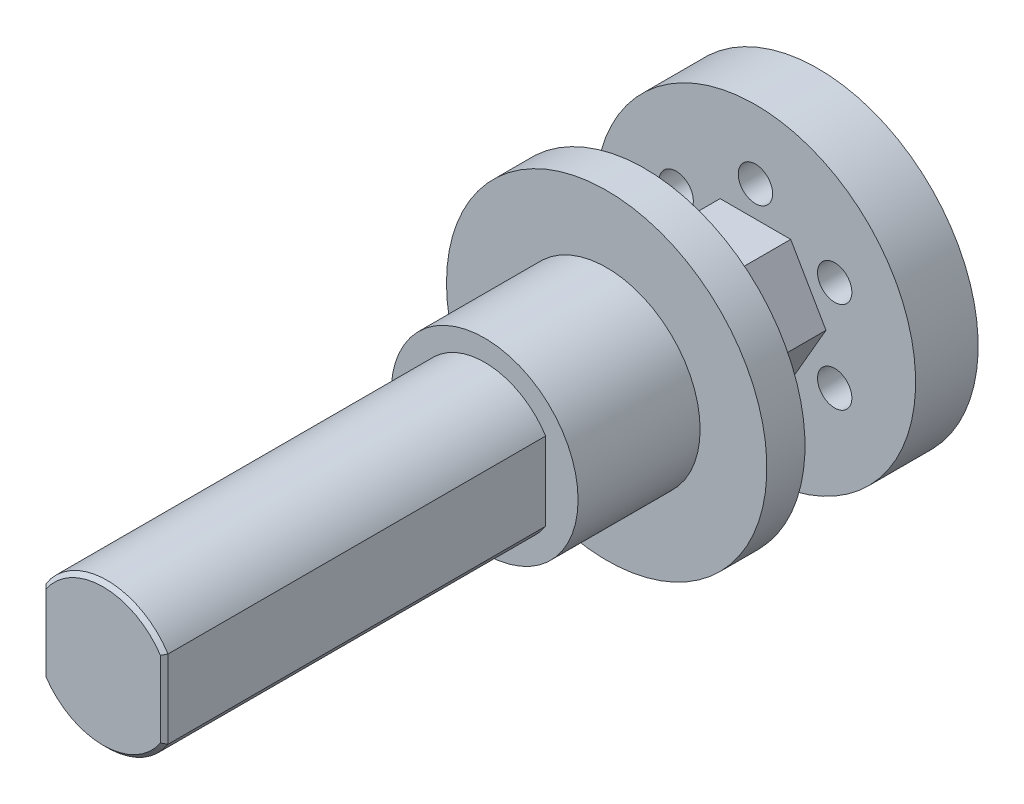
SolidWorks part; units mm, degrees
ref_plane "前视基准面" through (0, 0, 0) normal (0, 0, 1) x (1, 0, 0)
ref_plane "上视基准面" through (0, 0, 0) normal (0, 1, 0) x (1, 0, 0)
ref_plane "右视基准面" through (0, 0, 0) normal (1, 0, 0) x (0, 0, -1)
other "Configuration Table"
sketch "草图1" plane through (0, 0, 0) normal (0, 0, 1) x (1, 0, 0)
  circle A0 centre (0, 0) radius 9.25
  dimension "D1" = 18.5
extrude "凸台-拉伸1" add sketch "草图1" along normal blind 89.5 contours A0
ref_plane "基准面1" through (11.75, 0, 0) normal (-1, 0, 0) x (0, 0, 1)
ref_plane "基准面2" through (0, 0, 39.5) normal (0, 0, 1) x (1, 0, 0)
sketch "草图4" plane through (0, 0, 39.5) normal (0, 0, 1) x (1, 0, 0)
  circle A0 centre (0, 0) radius 12.25
  dimension "D1" = 24.5
extrude "凸台-拉伸2" add sketch "草图4" against normal blind 16
sketch "草图5" plane through (0, 0, 23.5) normal (0, 0, -1) x (-1, 0, 0)
  circle A0 centre (0, 0) radius 21
  dimension "D1" = 42
extrude "凸台-拉伸3" add sketch "草图5" along normal blind 5
sketch "草图6" plane through (0, 0, 0) normal (0, 0, -1) x (-1, 0, 0)
  circle A0 centre (0, 0) radius 21
  circle A1 centre (0, 0) radius 12 construction
  circle A2 centre (0, 12) radius 2.25
  circle A3 centre (0, 0) radius 21
  circle A4 centre (0, 0) radius 21
  circle A5 centre (0, 0) radius 21
  circle A6 centre (0, 0) radius 21
  circle A7 centre (0, 0) radius 21
  circle A8 centre (10.3923, 6) radius 2.25
  circle A9 centre (10.3923, -6) radius 2.25
  circle A10 centre (0, -12) radius 2.25
  circle A11 centre (-10.3923, -6) radius 2.25
  circle A12 centre (-10.3923, 6) radius 2.25
  point P14 (0, 0)
  point P25 (0, 0)
  dimension "D1" = 42
  dimension "D2" = 24
  dimension "D3" = 4.5
  dimension "D4" = 6
  dimension "D5" = 6
extrude "凸台-拉伸4" add sketch "草图6" along normal blind 4.2 and the other way blind 4 contours A0 | A12 | A2 | A8 | A9 | A10 | A11
sketch "草图7" plane through (0, 0, -4.2) normal (0, 0, -1) x (-1, 0, 0)
  circle A0 centre (0, 0) radius 20
  dimension "D1" = 40
extrude "切除-拉伸1" cut sketch "草图7" against normal blind 2
sketch "草图8" plane through (0, 0, 18.5) normal (0, 0, -1) x (-1, 0, 0)
  line L0 (-9.25, 0) -> (-4.625, -8.0107)
  line L1 (-4.625, -8.0107) -> (4.625, -8.0107)
  line L2 (4.625, -8.0107) -> (9.25, 0)
  line L3 (9.25, 0) -> (4.625, 8.0107)
  line L4 (4.625, 8.0107) -> (-4.625, 8.0107)
  line L5 (-4.625, 8.0107) -> (-9.25, 0)
  circle A0 centre (0, 0) radius 9.25 construction
  dimension "D1" = 18.5
  dimension "D2" = 120
extrude "切除-拉伸4" cut sketch "草图8" along normal up to surface (14.5 mm away) flip side to cut up to face at (-9.25, 0, 4)
sketch "草图11" plane through (0, 0, 39.5) normal (0, 0, 1) x (1, 0, 0)
  circle A0 centre (0, 0) radius 9.5
  dimension "D1" = 19
extrude "凸台-拉伸5" add sketch "草图11" along normal up to surface (50 mm away) up to face at (9.25, 0, 89.5)
sketch "草图13" plane through (0, 0, 89.5) normal (0, 0, 1) x (1, 0, 0)
  line L0 (-8, 5.1235) -> (-8, -5.1235)
  line L1 (-8, -5.1235) -> (8, -5.1235) construction
  line L2 (8, -5.1235) -> (8, 5.1235)
  line L3 (8, 5.1235) -> (-8, 5.1235) construction
  circle A0 centre (0, 0) radius 9.5 construction
  circle A1 centre (0, 0) radius 9.5 construction
  arc A2 (-8, 5.1235) -> (8, 5.1235) centre (0, 0) cw
  arc A3 (-8, -5.1235) -> (8, -5.1235) centre (0, 0) ccw
  dimension "D1" = 8
extrude "切除-拉伸-薄壁1" cut sketch "草图13" against normal up to surface (50 mm away) flip side to cut thin
chamfer "倒角1" distance 0.5 angle 45 4 edges at (8, 0, 89.5) (0, 9.5, 89.5) (0, -9.5, 89.5) (-8, 0, 89.5)
